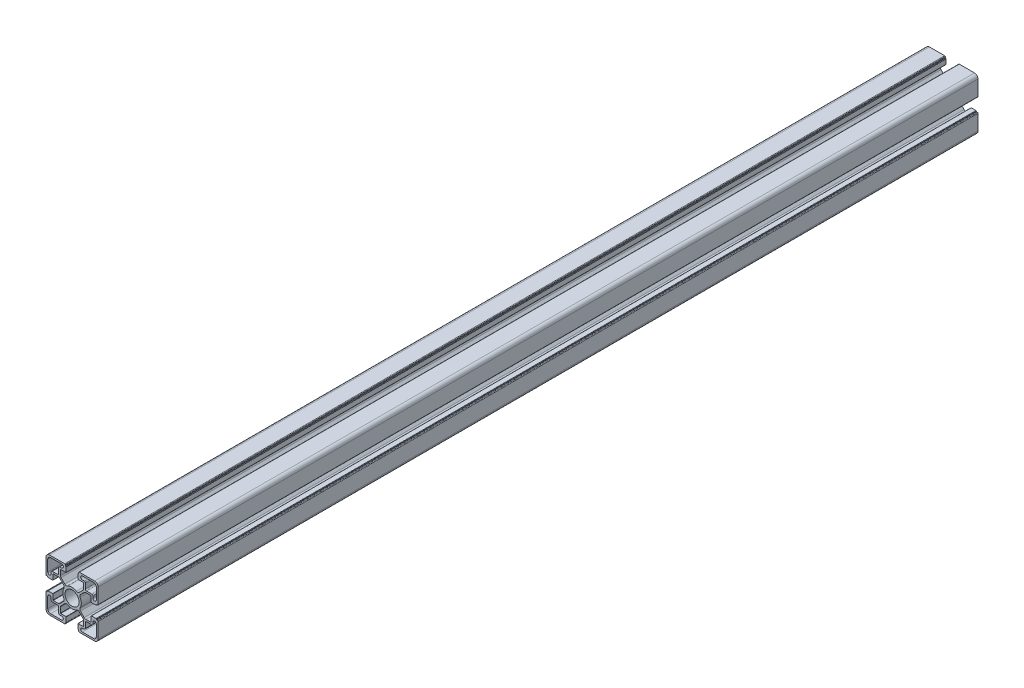
SolidWorks part; units mm, degrees
ref_plane "Front Plane" through (0, 0, 0) normal (0, 0, 1) x (1, 0, 0)
ref_plane "Top Plane" through (0, 0, 0) normal (0, 1, 0) x (1, 0, 0)
ref_plane "Right Plane" through (0, 0, 0) normal (1, 0, 0) x (0, 0, -1)
sketch "Sketch1" plane through (0, 0, 0) normal (0, 0, 1) x (1, 0, 0)
  line L3 (-22.5, 19.5) -> (-22.5, 6.3)
  line L4 (-20.7, 5) -> (-16.7, 5)
  line L5 (-16.5, 5.2) -> (-16.5, 9.8)
  line L6 (-16.3, 10) -> (-11.8642, 10)
  line L7 (-10.4924, 9.4318) -> (-7.2967, 6.236)
  line L8 (-21, 18.5) -> (-21, 9)
  line L9 (-16.5, 5) -> (-16.5, 10) construction
  line L10 (-18, 9) -> (-18, 10.5)
  line L11 (-17, 11.5) -> (-12.5, 11.5)
  line L12 (-22, 5.8) -> (-21.3, 5.8)
  line L13 (-21, 5.5) -> (-21, 5.3)
  line L14 (-21, 22.5) -> (-21, 6.5) construction
  line L15 (-18, 11.5) -> (-10.4393, 11.5) construction
  line L16 (-10.4393, 11.5) -> (-5.1016, 6.1623) construction
  line L17 (-18, 6.5) -> (-18, 11.5) construction
  line L18 (-22.5, 22.5) -> (-22.5, 5) construction
  line L19 (-22.5, 5) -> (-16.5, 5) construction
  line L20 (-21, 6.5) -> (-18, 6.5) construction
  line L21 (-16.5, 10) -> (-11.0607, 10) construction
  line L22 (-11.0607, 10) -> (-6.1623, 5.1016) construction
  line L23 (-5.5, 21) -> (-5.3, 21)
  line L24 (-5.8, 22) -> (-5.8, 21.3)
  line L25 (-11.5, 17) -> (-11.5, 12.5)
  line L26 (-9, 18) -> (-10.5, 18)
  line L27 (-18.5, 21) -> (-9, 21)
  line L28 (-9.4318, 10.4924) -> (-6.236, 7.2967)
  line L29 (-10, 16.3) -> (-10, 11.8642)
  line L30 (-5.2, 16.5) -> (-9.8, 16.5)
  line L31 (-5, 20.7) -> (-5, 16.7)
  line L32 (-19.5, 22.5) -> (-6.3, 22.5)
  line L33 (19.5, 22.5) -> (6.3, 22.5)
  line L34 (5, 20.7) -> (5, 16.7)
  line L35 (5.2, 16.5) -> (9.8, 16.5)
  line L36 (10, 16.3) -> (10, 11.8642)
  line L37 (9.4318, 10.4924) -> (6.236, 7.2967)
  line L38 (18.5, 21) -> (9, 21)
  line L39 (9, 18) -> (10.5, 18)
  line L40 (11.5, 17) -> (11.5, 12.5)
  line L41 (5.8, 22) -> (5.8, 21.3)
  line L42 (5.5, 21) -> (5.3, 21)
  line L43 (21, 5.5) -> (21, 5.3)
  line L44 (22, 5.8) -> (21.3, 5.8)
  line L45 (17, 11.5) -> (12.5, 11.5)
  line L46 (18, 9) -> (18, 10.5)
  line L47 (21, 18.5) -> (21, 9)
  line L48 (10.4924, 9.4318) -> (7.2967, 6.236)
  line L49 (16.3, 10) -> (11.8642, 10)
  line L50 (16.5, 5.2) -> (16.5, 9.8)
  line L51 (20.7, 5) -> (16.7, 5)
  line L52 (22.5, 19.5) -> (22.5, 6.3)
  line L53 (22.5, -19.5) -> (22.5, -6.3)
  line L54 (20.7, -5) -> (16.7, -5)
  line L55 (16.5, -5.2) -> (16.5, -9.8)
  line L56 (16.3, -10) -> (11.8642, -10)
  line L57 (10.4924, -9.4318) -> (7.2967, -6.236)
  line L58 (21, -18.5) -> (21, -9)
  line L59 (18, -9) -> (18, -10.5)
  line L60 (17, -11.5) -> (12.5, -11.5)
  line L61 (22, -5.8) -> (21.3, -5.8)
  line L62 (21, -5.5) -> (21, -5.3)
  line L63 (5.5, -21) -> (5.3, -21)
  line L64 (5.8, -22) -> (5.8, -21.3)
  line L65 (11.5, -17) -> (11.5, -12.5)
  line L66 (9, -18) -> (10.5, -18)
  line L67 (18.5, -21) -> (9, -21)
  line L68 (9.4318, -10.4924) -> (6.236, -7.2967)
  line L69 (10, -16.3) -> (10, -11.8642)
  line L70 (5.2, -16.5) -> (9.8, -16.5)
  line L71 (5, -20.7) -> (5, -16.7)
  line L72 (19.5, -22.5) -> (6.3, -22.5)
  line L73 (-19.5, -22.5) -> (-6.3, -22.5)
  line L74 (-5, -20.7) -> (-5, -16.7)
  line L75 (-5.2, -16.5) -> (-9.8, -16.5)
  line L76 (-10, -16.3) -> (-10, -11.8642)
  line L77 (-9.4318, -10.4924) -> (-6.236, -7.2967)
  line L78 (-18.5, -21) -> (-9, -21)
  line L79 (-9, -18) -> (-10.5, -18)
  line L80 (-11.5, -17) -> (-11.5, -12.5)
  line L81 (-5.8, -22) -> (-5.8, -21.3)
  line L82 (-5.5, -21) -> (-5.3, -21)
  line L83 (-21, -5.5) -> (-21, -5.3)
  line L84 (-22, -5.8) -> (-21.3, -5.8)
  line L85 (-17, -11.5) -> (-12.5, -11.5)
  line L86 (-18, -9) -> (-18, -10.5)
  line L87 (-21, -18.5) -> (-21, -9)
  line L88 (-10.4924, -9.4318) -> (-7.2967, -6.236)
  line L89 (-16.3, -10) -> (-11.8642, -10)
  line L90 (-16.5, -5.2) -> (-16.5, -9.8)
  line L91 (-20.7, -5) -> (-16.7, -5)
  line L92 (-22.5, -19.5) -> (-22.5, -6.3)
  arc A0 (0, 6.1) -> (-6.1, 0) centre (0, 0) ccw
  arc A1 (-6.9766, 3.9149) -> (-8, 0) centre (0, 0) ccw
  arc A2 (-21, 9) -> (-18, 9) centre (-19.5, 9) ccw
  arc A3 (-22, 5.8) -> (-22.5, 6.3) centre (-22, 6.3) cw
  arc A4 (-21, 5.3) -> (-20.7, 5) centre (-20.7, 5.3) ccw
  arc A5 (-21.3, 5.8) -> (-21, 5.5) centre (-21.3, 5.5) cw
  arc A6 (-16.7, 5) -> (-16.5, 5.2) centre (-16.7, 5.2) ccw
  arc A7 (-16.5, 9.8) -> (-16.3, 10) centre (-16.3, 9.8) cw
  arc A8 (-7.2967, 6.236) -> (-6.9766, 3.9149) centre (-8.6685, 4.8643) cw
  arc A9 (-11.8642, 10) -> (-10.4924, 9.4318) centre (-11.8642, 8.06) cw
  arc A10 (-18, 10.5) -> (-17, 11.5) centre (-17, 10.5) cw
  arc A11 (-10.5, 18) -> (-11.5, 17) centre (-10.5, 17) ccw
  arc A12 (-10, 11.8642) -> (-9.4318, 10.4924) centre (-8.06, 11.8642) ccw
  arc A13 (-6.236, 7.2967) -> (-3.9149, 6.9766) centre (-4.8643, 8.6685) ccw
  arc A14 (-9.8, 16.5) -> (-10, 16.3) centre (-9.8, 16.3) ccw
  arc A15 (-5, 16.7) -> (-5.2, 16.5) centre (-5.2, 16.7) cw
  arc A16 (-5.8, 21.3) -> (-5.5, 21) centre (-5.5, 21.3) ccw
  arc A17 (-5.3, 21) -> (-5, 20.7) centre (-5.3, 20.7) cw
  arc A18 (-5.8, 22) -> (-6.3, 22.5) centre (-6.3, 22) ccw
  arc A19 (-9, 21) -> (-9, 18) centre (-9, 19.5) cw
  arc A20 (-3.9149, 6.9766) -> (0, 8) centre (0, 0) cw
  arc A21 (-21, 18.5) -> (-18.5, 21) centre (-18.5, 18.5) cw
  arc A22 (-22.5, 19.5) -> (-19.5, 22.5) centre (-19.5, 19.5) cw
  arc A23 (-12.5, 11.5) -> (-11.5, 12.5) centre (-12.5, 12.5) ccw
  arc A24 (6.1, 0) -> (0, 6.1) centre (0, 0) ccw
  arc A25 (3.9149, 6.9766) -> (0, 8) centre (0, 0) ccw
  arc A26 (9, 21) -> (9, 18) centre (9, 19.5) ccw
  arc A27 (5.8, 22) -> (6.3, 22.5) centre (6.3, 22) cw
  arc A28 (5.3, 21) -> (5, 20.7) centre (5.3, 20.7) ccw
  arc A29 (5.8, 21.3) -> (5.5, 21) centre (5.5, 21.3) cw
  arc A30 (5, 16.7) -> (5.2, 16.5) centre (5.2, 16.7) ccw
  arc A31 (9.8, 16.5) -> (10, 16.3) centre (9.8, 16.3) cw
  arc A32 (6.236, 7.2967) -> (3.9149, 6.9766) centre (4.8643, 8.6685) cw
  arc A33 (10, 11.8642) -> (9.4318, 10.4924) centre (8.06, 11.8642) cw
  arc A34 (10.5, 18) -> (11.5, 17) centre (10.5, 17) cw
  arc A35 (18, 10.5) -> (17, 11.5) centre (17, 10.5) ccw
  arc A36 (11.8642, 10) -> (10.4924, 9.4318) centre (11.8642, 8.06) ccw
  arc A37 (7.2967, 6.236) -> (6.9766, 3.9149) centre (8.6685, 4.8643) ccw
  arc A38 (16.5, 9.8) -> (16.3, 10) centre (16.3, 9.8) ccw
  arc A39 (16.7, 5) -> (16.5, 5.2) centre (16.7, 5.2) cw
  arc A40 (21.3, 5.8) -> (21, 5.5) centre (21.3, 5.5) ccw
  arc A41 (21, 5.3) -> (20.7, 5) centre (20.7, 5.3) cw
  arc A42 (22, 5.8) -> (22.5, 6.3) centre (22, 6.3) ccw
  arc A43 (21, 9) -> (18, 9) centre (19.5, 9) cw
  arc A44 (6.9766, 3.9149) -> (8, 0) centre (0, 0) cw
  arc A45 (18.5, 21) -> (21, 18.5) centre (18.5, 18.5) cw
  arc A46 (19.5, 22.5) -> (22.5, 19.5) centre (19.5, 19.5) cw
  arc A47 (11.5, 12.5) -> (12.5, 11.5) centre (12.5, 12.5) ccw
  arc A48 (0, -6.1) -> (6.1, 0) centre (0, 0) ccw
  arc A49 (6.9766, -3.9149) -> (8, 0) centre (0, 0) ccw
  arc A50 (21, -9) -> (18, -9) centre (19.5, -9) ccw
  arc A51 (22, -5.8) -> (22.5, -6.3) centre (22, -6.3) cw
  arc A52 (21, -5.3) -> (20.7, -5) centre (20.7, -5.3) ccw
  arc A53 (21.3, -5.8) -> (21, -5.5) centre (21.3, -5.5) cw
  arc A54 (16.7, -5) -> (16.5, -5.2) centre (16.7, -5.2) ccw
  arc A55 (16.5, -9.8) -> (16.3, -10) centre (16.3, -9.8) cw
  arc A56 (7.2967, -6.236) -> (6.9766, -3.9149) centre (8.6685, -4.8643) cw
  arc A57 (11.8642, -10) -> (10.4924, -9.4318) centre (11.8642, -8.06) cw
  arc A58 (18, -10.5) -> (17, -11.5) centre (17, -10.5) cw
  arc A59 (10.5, -18) -> (11.5, -17) centre (10.5, -17) ccw
  arc A60 (10, -11.8642) -> (9.4318, -10.4924) centre (8.06, -11.8642) ccw
  arc A61 (6.236, -7.2967) -> (3.9149, -6.9766) centre (4.8643, -8.6685) ccw
  arc A62 (9.8, -16.5) -> (10, -16.3) centre (9.8, -16.3) ccw
  arc A63 (5, -16.7) -> (5.2, -16.5) centre (5.2, -16.7) cw
  arc A64 (5.8, -21.3) -> (5.5, -21) centre (5.5, -21.3) ccw
  arc A65 (5.3, -21) -> (5, -20.7) centre (5.3, -20.7) cw
  arc A66 (5.8, -22) -> (6.3, -22.5) centre (6.3, -22) ccw
  arc A67 (9, -21) -> (9, -18) centre (9, -19.5) cw
  arc A68 (3.9149, -6.9766) -> (0, -8) centre (0, 0) cw
  arc A69 (21, -18.5) -> (18.5, -21) centre (18.5, -18.5) cw
  arc A70 (22.5, -19.5) -> (19.5, -22.5) centre (19.5, -19.5) cw
  arc A71 (12.5, -11.5) -> (11.5, -12.5) centre (12.5, -12.5) ccw
  arc A72 (-6.1, 0) -> (0, -6.1) centre (0, 0) ccw
  arc A73 (-3.9149, -6.9766) -> (0, -8) centre (0, 0) ccw
  arc A74 (-9, -21) -> (-9, -18) centre (-9, -19.5) ccw
  arc A75 (-5.8, -22) -> (-6.3, -22.5) centre (-6.3, -22) cw
  arc A76 (-5.3, -21) -> (-5, -20.7) centre (-5.3, -20.7) ccw
  arc A77 (-5.8, -21.3) -> (-5.5, -21) centre (-5.5, -21.3) cw
  arc A78 (-5, -16.7) -> (-5.2, -16.5) centre (-5.2, -16.7) ccw
  arc A79 (-9.8, -16.5) -> (-10, -16.3) centre (-9.8, -16.3) cw
  arc A80 (-6.236, -7.2967) -> (-3.9149, -6.9766) centre (-4.8643, -8.6685) cw
  arc A81 (-10, -11.8642) -> (-9.4318, -10.4924) centre (-8.06, -11.8642) cw
  arc A82 (-10.5, -18) -> (-11.5, -17) centre (-10.5, -17) cw
  arc A83 (-18, -10.5) -> (-17, -11.5) centre (-17, -10.5) ccw
  arc A84 (-11.8642, -10) -> (-10.4924, -9.4318) centre (-11.8642, -8.06) ccw
  arc A85 (-7.2967, -6.236) -> (-6.9766, -3.9149) centre (-8.6685, -4.8643) ccw
  arc A86 (-16.5, -9.8) -> (-16.3, -10) centre (-16.3, -9.8) ccw
  arc A87 (-16.7, -5) -> (-16.5, -5.2) centre (-16.7, -5.2) cw
  arc A88 (-21.3, -5.8) -> (-21, -5.5) centre (-21.3, -5.5) ccw
  arc A89 (-21, -5.3) -> (-20.7, -5) centre (-20.7, -5.3) cw
  arc A90 (-22, -5.8) -> (-22.5, -6.3) centre (-22, -6.3) ccw
  arc A91 (-21, -9) -> (-18, -9) centre (-19.5, -9) cw
  arc A92 (-6.9766, -3.9149) -> (-8, 0) centre (0, 0) cw
  arc A93 (-18.5, -21) -> (-21, -18.5) centre (-18.5, -18.5) cw
  arc A94 (-19.5, -22.5) -> (-22.5, -19.5) centre (-19.5, -19.5) cw
  arc A95 (-11.5, -12.5) -> (-12.5, -11.5) centre (-12.5, -12.5) ccw
  point P24 (-5.8, 21)
  point P32 (-22.5, 5.8)
  point P35 (-21, 5)
  point P38 (-21, 5.8)
  point P83 (-5, 21)
  point P84 (-5.8, 22.5)
  point P87 (-21, 21)
  point P93 (-11.5, 11.5)
  point P102 (21, 5.8)
  point P158 (21, 5)
  point P159 (22.5, 5.8)
  point P172 (5.8, -21)
  point P228 (5, -21)
  point P229 (5.8, -22.5)
  point P242 (-21, -5.8)
  point P298 (-21, -5)
  point P299 (-22.5, -5.8)
  dimension "D11" = 0.5
  dimension "D12" = 0.3
  dimension "D13" = 0.2
  dimension "D14" = 0.2
  dimension "D6" = 1.94
  dimension "D15" = 1
  dimension "D16" = 2.5
  dimension "D4" = 3
  dimension "D17" = 1
  dimension "D5" = 0.8
  dimension "D7" = 1.5
  dimension "D9" = 1.5
  dimension "D10" = 4
  dimension "D18" = 4
extrude "Boss-Extrude1" add sketch "Sketch1" along normal blind 429.35
scale "Scale2" scale about centroid uniform scaling no x scale factor 0.564444 y scale factor 0.564444 z scale factor 1
